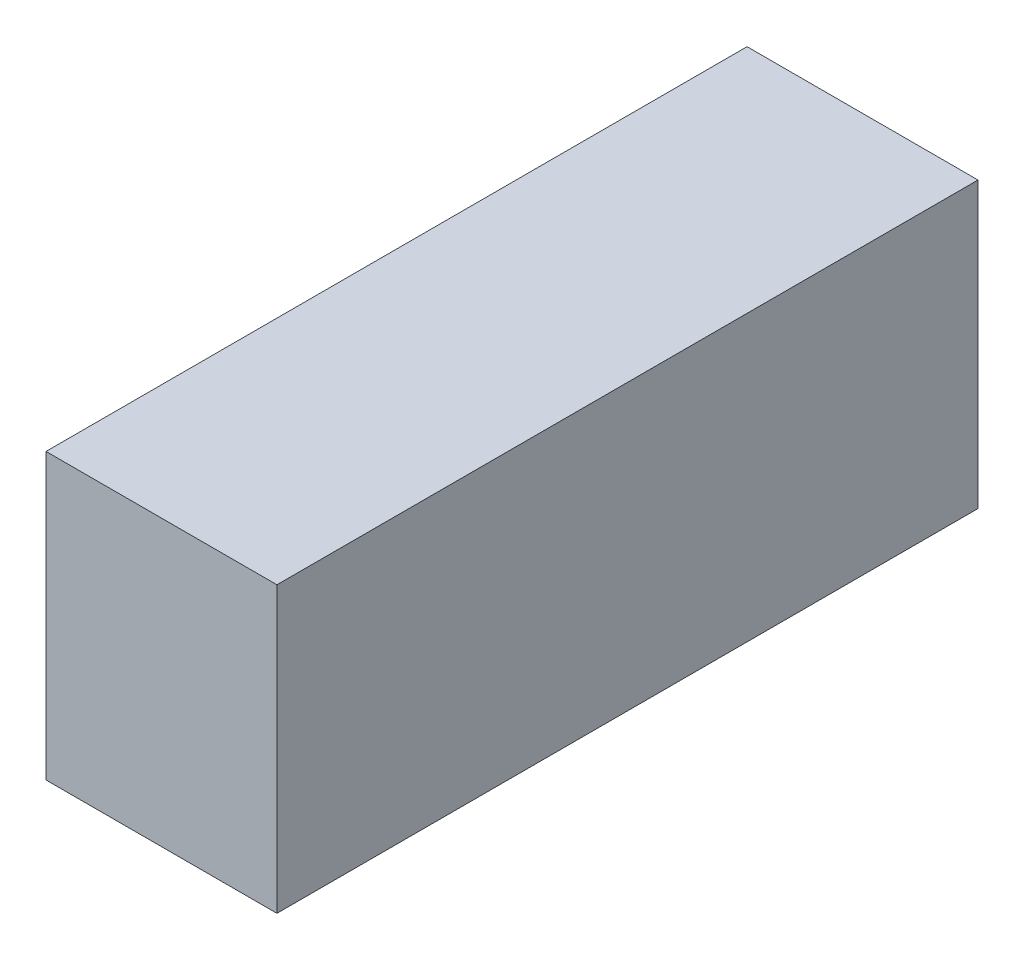
SolidWorks part; units mm, degrees
material "EPDM 60 Durometer"
ref_plane "Ebene vorne" through (0, 0, 0) normal (0, 0, 1) x (1, 0, 0)
ref_plane "Ebene oben" through (0, 0, 0) normal (0, 1, 0) x (1, 0, 0)
ref_plane "Ebene rechts" through (0, 0, 0) normal (1, 0, 0) x (0, 0, -1)
sketch "Skizze1" plane through (0, 0, 0) normal (0, 0, 1) x (1, 0, 0)
  line L1 (-28, -34.5) -> (28, -34.5)
  line L2 (-28, -34.5) -> (-28, 34.5)
  line L3 (-28, 34.5) -> (28, 34.5)
  line L4 (28, -34.5) -> (28, 34.5)
  line L5 (-28, -34.5) -> (28, 34.5) construction
  line L6 (-28, 34.5) -> (28, -34.5) construction
  point P0 (0, 0)
  dimension "D1" = 56
  dimension "D2" = 69
extrude "Aufsatz-Linear austragen1" add sketch "Skizze1" along normal blind 170
